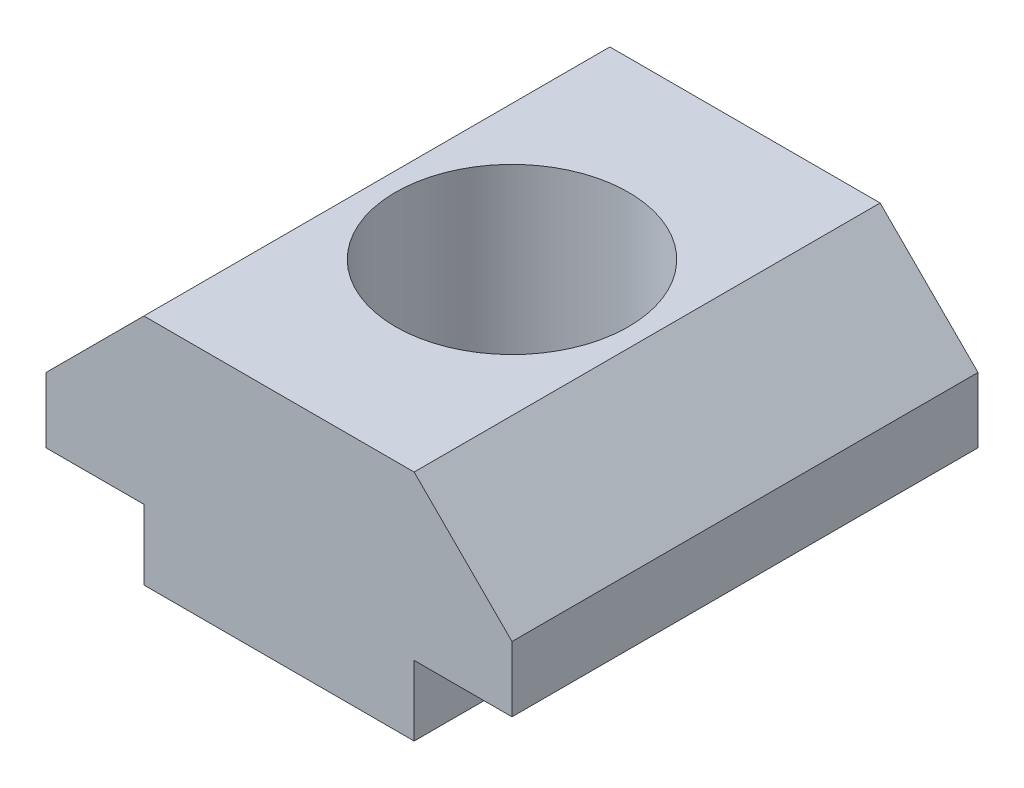
SolidWorks part; units mm, degrees
ref_plane "前视基准面" through (0, 0, 0) normal (0, 0, 1) x (1, 0, 0)
ref_plane "上视基准面" through (0, 0, 0) normal (0, 1, 0) x (1, 0, 0)
ref_plane "右视基准面" through (0, 0, 0) normal (1, 0, 0) x (0, 0, -1)
sketch "草图1" plane through (0, 0, 0) normal (0, 0, 1) x (1, 0, 0)
  line L0 (-2.9, 0) -> (2.9, 0)
  line L1 (2.9, 0) -> (2.9, 1.5)
  line L2 (2.9, 1.5) -> (5, 1.5)
  line L3 (5, 1.5) -> (5, 2.9)
  line L4 (5, 2.9) -> (2.9, 5)
  line L5 (2.9, 5) -> (-2.9, 5)
  line L6 (-2.9, 5) -> (-5, 2.9)
  line L7 (-5, 2.9) -> (-5, 1.5)
  line L8 (-5, 1.5) -> (-2.9, 1.5)
  line L9 (-2.9, 1.5) -> (-2.9, 0)
  line L10 (0, -82.6522) -> (0, 4049.9602) construction
  point P14 (0, 0)
  point P17 (-5, 2.2)
  dimension "D1" = 5.8
  dimension "D2" = 5
  dimension "D3" = 10
  dimension "D4" = 135
  dimension "D5" = 1.5
extrude "凸台-拉伸1" add sketch "草图1" against normal blind 10
sketch "草图4" plane through (0, 5, 0) normal (0, 1, 0) x (1, 0, 0)
  line L0 (0, -990) -> (0, 49010) construction
  line L1 (2.9, 10) -> (-2.9, 10) construction
  line L2 (-995.1, 5) -> (49004.9, 5) construction
  line L3 (5, 10) -> (5, 0) construction
  circle A0 centre (0, 5) radius 2.5
  point P5 (0, 10)
  point P10 (5, 5)
  dimension "D1" = 5
extrude "切除-拉伸1" cut sketch "草图4" against normal through all
